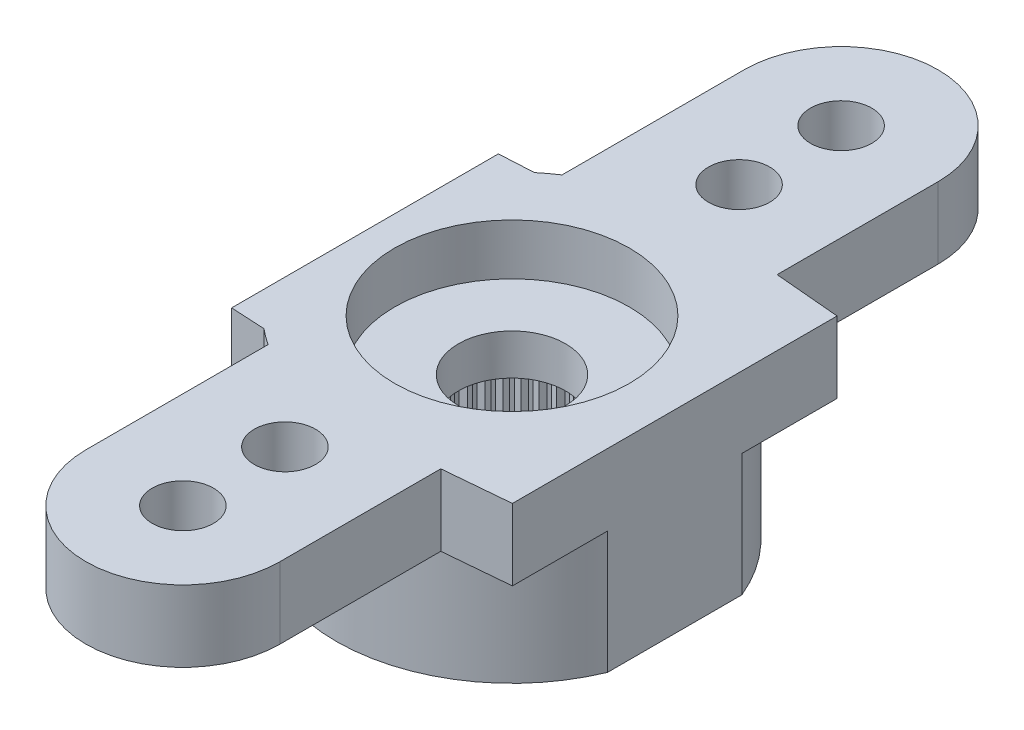
SolidWorks part; units mm, degrees
other "Markup1"
sketch "Sketch2" plane through (18.45, -3.8, 8.35) normal (0.5467, -0.076, 0.8339) x (0.3087, -0.9075, -0.285)
other "Markup2"
sketch "Sketch3" plane through (18.45, 0, 8.35) normal (0.5774, 0.5773, 0.5774) x (0.7071, 0, -0.7071)
material "PVC Rígido"
ref_plane "Plano frontal" through (0, 0, 0) normal (0, 0, 1) x (1, 0, 0)
ref_plane "Plano superior" through (0, 0, 0) normal (0, 1, 0) x (1, 0, 0)
ref_plane "Plano direito" through (0, 0, 0) normal (1, 0, 0) x (0, 0, -1)
sketch "Esboço1" plane through (0, 0, 0) normal (0, 1, 0) x (1, 0, 0)
  line L0 (0, 0) -> (-14.05, 0) construction
  line L1 (-14.1591, 1.997) -> (-2.2091, 2.65)
  line L2 (-2.2091, -2.65) -> (-14.1591, -1.997)
  arc A0 (-2.2091, -2.65) -> (-2.2091, 2.65) centre (0, 0) ccw
  arc A1 (-14.1591, 1.997) -> (-14.1591, -1.997) centre (-14.05, 0) ccw
  dimension "D1" = 6.9
  dimension "D2" = 4
  dimension "D3" = 19.5
  dimension "D4" = 5.3
extrude "Ressalto-extrusão1" add sketch "Esboço1" against normal blind 1.4
sketch "Esboço2" plane through (0, -1.4, 0) normal (0, -1, 0) x (1, 0, 0)
  arc A0 (-2.2091, -2.65) -> (-2.2091, 2.65) centre (0, 0) ccw construction
  circle A1 centre (0, 0) radius 3.45
extrude "Ressalto-extrusão2" add sketch "Esboço2" along normal offset from surface (2.4 mm away) 3.8 up to face at (-7.242, 0, 0)
hole_wizard "Furo1" positions "Esboço9" profile "Esboço10" legacy end condition through all
sketch "Esboço9" plane through (0, 0, 0) normal (0, 1, 0) x (1, 0, 0)
  line L1 (-14.45, 0) -> (0, 0) construction
  arc A2 (-14.1591, 1.997) -> (-14.1591, -1.997) centre (-14.05, 0) ccw construction
  point P0 (-14.45, 0)
  point P19 (-16.05, 0)
  dimension "D1" = 1.6
sketch "Esboço10" plane through (-14.45, 0, 0) normal (1, 0, 0) x (0, 0, 1)
  line L0 (0, 0) -> (0, 3.8)
  line L1 (0, 3.8) -> (0.6, 3.8)
  line L2 (0.6, 3.8) -> (0.6, 0)
  line L3 (0.6, 0) -> (0, 0)
  line L4 (0, 110) -> (0, -10) construction
  dimension "Diameter" = 1.2
  dimension "Depth" = 3.8
pattern_linear "Padrão linear1" count 6 spacing 2 along (1, 0, 0) of "Furo1"
sketch "Esboço12" plane through (0, 0, 0) normal (0, 1, 0) x (1, 0, 0)
  line L0 (0.3041, 3.4366) -> (16.6263, 1.9922)
  line L1 (16.6263, -1.9922) -> (0.3041, -3.4366)
  arc A0 (-2.2091, -2.65) -> (-2.2091, 2.65) centre (0, 0) ccw construction
  arc A1 (0.3041, -3.4366) -> (0.3041, 3.4366) centre (0, 0) ccw
  arc A2 (16.6263, 1.9922) -> (16.6263, -1.9922) centre (16.45, 0) cw
  arc A3 (-14.1591, 1.997) -> (-14.1591, -1.997) centre (-14.05, 0) ccw construction
  dimension "D1" = 2
  dimension "D2" = 34.5
extrude "Ressalto-extrusão3" add sketch "Esboço12" against normal up to surface (1.4 mm away) up to face at (-12.45, -1.4, 0.6)
hole_wizard "Furo2" positions "Esboço13" profile "Esboço14" legacy end condition through all
sketch "Esboço13" plane through (0, 0, 0) normal (0, 1, 0) x (1, 0, 0)
  line L0 (0, 0) -> (16.85, 0) construction
  arc A0 (16.6263, -1.9922) -> (16.6263, 1.9922) centre (16.45, 0) ccw construction
  point P0 (16.85, 0)
  point P6 (18.45, 0)
  dimension "D1" = 1.6
sketch "Esboço14" plane through (16.85, 0, 0) normal (1, 0, 0) x (0, 0, 1)
  line L0 (0, 0) -> (0, 3.8)
  line L1 (0, 3.8) -> (0.6, 3.8)
  line L2 (0.6, 3.8) -> (0.6, 0)
  line L3 (0.6, 0) -> (0, 0)
  line L4 (0, 110) -> (0, -10) construction
  dimension "Diameter" = 1.2
  dimension "Depth" = 3.8
pattern_linear "Padrão linear2" count 7 spacing 2 along (-1, 0, 0) of "Furo2"
sketch "Esboço16" plane through (0, 0, 0) normal (0, 1, 0) x (1, 0, 0)
  line L0 (0, -6.45) -> (0, 6.45) construction
  line L1 (-1.9, -6.45) -> (-1.9, 6.45)
  line L2 (1.9, -6.45) -> (1.9, 6.45)
  arc A0 (-1.9, -6.45) -> (1.9, -6.45) centre (0, -6.45) ccw
  arc A1 (1.9, 6.45) -> (-1.9, 6.45) centre (0, 6.45) ccw
  point P2 (0, 0)
  dimension "D2" = 16.7
  dimension "D1" = 3.8
extrude "Ressalto-extrusão4" add sketch "Esboço16" against normal up to surface (1.4 mm away) up to face at (14.85, -1.4, 0.6)
hole_wizard "Furo3" positions "Esboço17" profile "Esboço18" legacy end condition through all
sketch "Esboço17" plane through (0, 0, 0) normal (0, 1, 0) x (1, 0, 0)
  point P0 (0, -6.45)
sketch "Esboço18" plane through (0, 0, 6.45) normal (1, 0, 0) x (0, 0, 1)
  line L0 (0, 0) -> (0, 3.8)
  line L1 (0, 3.8) -> (0.6, 3.8)
  line L2 (0.6, 3.8) -> (0.6, 0)
  line L3 (0.6, 0) -> (0, 0)
  line L4 (0, 110) -> (0, -10) construction
  dimension "Diameter" = 1.2
  dimension "Depth" = 3.8
pattern_linear "Padrão linear3" count 2 spacing 2 along (0, 0, -1) of "Furo3"
pattern_circular "PadrãoCircular1" count 2 over 360 about axis through (0, 0, 0) along (0, 1, 0) of "Padrão linear3", "Furo3"
hole_wizard "Furo4" positions "Esboço3" profile "Esboço4" legacy
sketch "Esboço3" plane through (0, -3.8, 0) normal (0, -1, 0) x (-1, 0, 0)
  point P0 (0, 0)
sketch "Esboço4" plane through (0, -3.8, 0) normal (1, 0, 0) x (0, 0, -1)
  line L0 (0, 0) -> (0, 2)
  line L1 (0, 2) -> (2.475, 2)
  line L2 (2.475, 2) -> (2.475, 0)
  line L3 (2.475, 0) -> (0, 0)
  line L4 (0, 110) -> (0, -10) construction
  dimension "Diameter" = 4.95
  dimension "Depth" = 2
hole_wizard "Furo5" positions "Esboço5" profile "Esboço6" legacy
sketch "Esboço5" plane through (0, 0, 0) normal (0, 1, 0) x (1, 0, 0)
  point P0 (0, 0)
sketch "Esboço6" plane through (0, 0, 0) normal (1, 0, 0) x (0, 0, 1)
  line L0 (0, 0) -> (0, 1)
  line L1 (0, 1) -> (2.3, 1)
  line L2 (2.3, 1) -> (2.3, 0)
  line L3 (2.3, 0) -> (0, 0)
  line L4 (0, 110) -> (0, -10) construction
  dimension "Diameter" = 4.6
  dimension "Depth" = 1
hole_wizard "Furo6" positions "Esboço7" profile "Esboço8" legacy end condition through all
sketch "Esboço7" plane through (0, 0, 0) normal (0, 1, 0) x (1, 0, 0)
  point P0 (0, 0)
sketch "Esboço8" plane through (0, 0, 0) normal (1, 0, 0) x (0, 0, 1)
  line L0 (0, 0) -> (0, 3.8)
  line L1 (0, 3.8) -> (1.05, 3.8)
  line L2 (1.05, 3.8) -> (1.05, 0)
  line L3 (1.05, 0) -> (0, 0)
  line L4 (0, 110) -> (0, -10) construction
  dimension "Diameter" = 2.1
  dimension "Depth" = 3.8
sketch "Esboço11" plane through (0, -3.8, 0) normal (0, -1, 0) x (1, 0, 0)
  line L0 (-0.0981, 2.4731) -> (0, 2.375)
  line L1 (0, 2.375) -> (0.0981, 2.4731)
  line L2 (0, 0) -> (0, 2.475) construction
  circle A0 centre (0, 0) radius 2.375 construction
  circle A1 centre (0, 0) radius 2.475
  arc A2 (0.0981, 2.4731) -> (-0.0981, 2.4731) centre (0, 0) ccw
  dimension "D3" = 4.75
  dimension "D2" = 0.1
  dimension "D1" = 0
extrude "Ressalto-extrusão5" add sketch "Esboço11" against normal up to surface (2 mm away) up to face at (0, -1.8, 1.05)
pattern_circular "PadrãoCircular2" count 60 over 360 about axis through (0, 0, 0) along (0, 1, 0) of "Ressalto-extrusão5"
sketch "Sketch4" plane through (0, 0, 0) normal (0, 1, 0) x (1, 0, 0)
  line L1 (-18.3758, 8.7877) -> (-2.8806, 8.7877)
  line L2 (-18.3758, 8.7877) -> (-18.3758, -8.2161)
  line L3 (-18.3758, -8.2161) -> (-2.8806, -8.2161)
  line L4 (-2.8806, 8.7877) -> (-2.8806, -8.2161)
  line L5 (3.1893, 8.7877) -> (20.1299, 8.7877)
  line L6 (3.1893, 8.7877) -> (3.1893, -7.3045)
  line L7 (3.1893, -7.3045) -> (20.1299, -7.3045)
  line L8 (20.1299, 8.7877) -> (20.1299, -7.3045)
extrude "Cut-Extrude1" cut sketch "Sketch4" against normal blind 10
